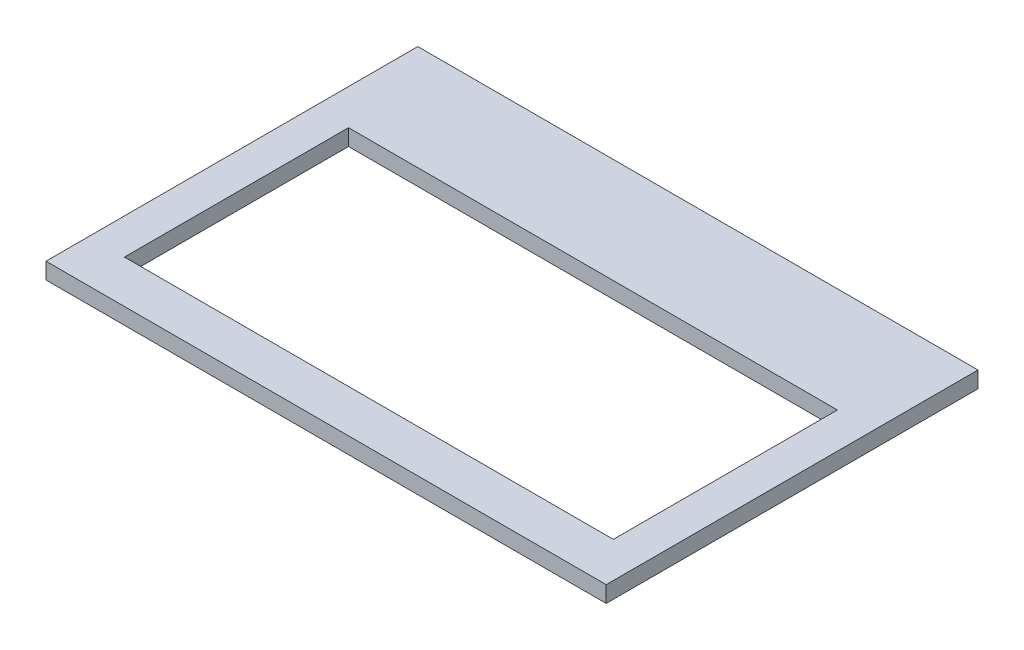
SolidWorks part; units mm, degrees
ref_plane "Płaszczyzna przednia" through (0, 0, 0) normal (0, 0, 1) x (1, 0, 0)
ref_plane "Płaszczyzna górna" through (0, 0, 0) normal (0, 1, 0) x (1, 0, 0)
ref_plane "Płaszczyzna prawa" through (0, 0, 0) normal (1, 0, 0) x (0, 0, -1)
sketch "Szkic1" plane through (0, 0, 0) normal (0, 1, 0) x (1, 0, 0)
  line L1 (-275, -182.5) -> (275, -182.5)
  line L2 (-275, -182.5) -> (-275, 182.5)
  line L3 (-275, 182.5) -> (275, 182.5)
  line L4 (275, -182.5) -> (275, 182.5)
  line L5 (-275, -182.5) -> (275, 182.5) construction
  line L6 (-275, 182.5) -> (275, -182.5) construction
  point P0 (0, 0)
  dimension "D1" = 550
  dimension "D2" = 365
extrude "Dodanie-wyciągnięcie1" add sketch "Szkic1" along normal blind 16
sketch "Szkic2" plane through (0, 16, 0) normal (0, 1, 0) x (1, 0, 0)
  line L0 (-275, -182.5) -> (275, -182.5) construction
  line L1 (-240, 79.5) -> (240, 79.5)
  line L2 (-240, 79.5) -> (-240, -140.5)
  line L3 (-240, -140.5) -> (240, -140.5)
  line L4 (240, 79.5) -> (240, -140.5)
  line L8 (-275, 182.5) -> (-275, -182.5) construction
  point P4 (240, -30.5)
  dimension "D1" = 480
  dimension "D2" = 220
  dimension "D3" = 152
  dimension "D4" = 35
extrude "Wytnij-wyciągnięcie1" cut sketch "Szkic2" against normal blind 16
